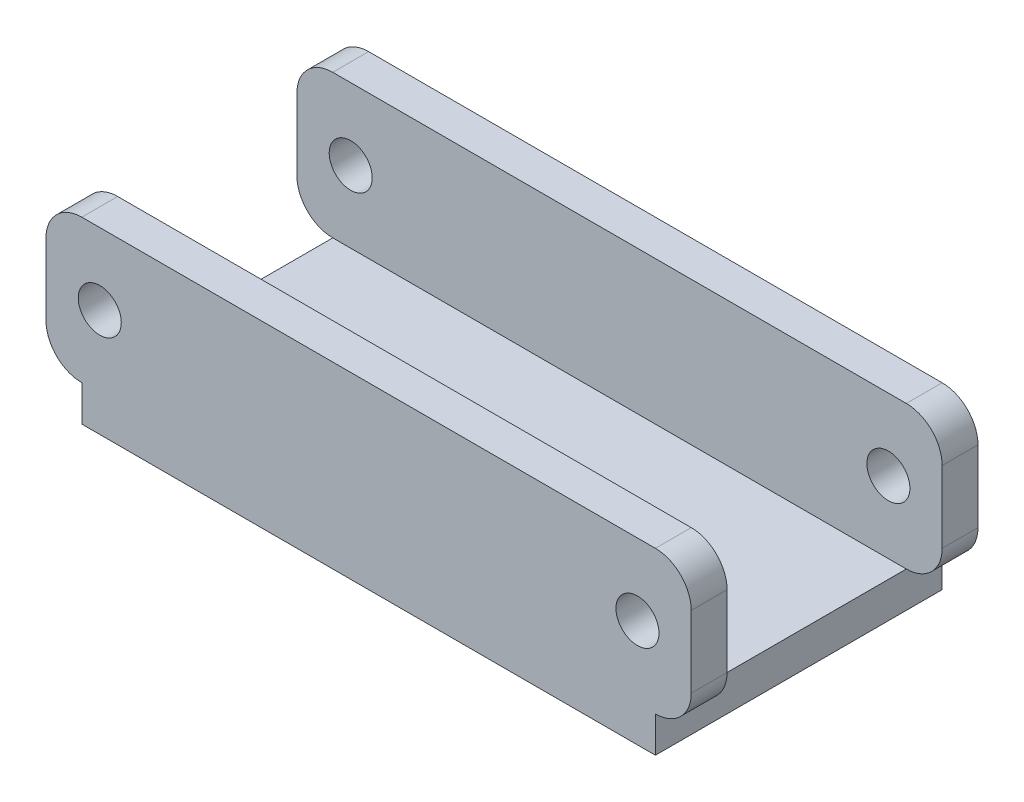
SolidWorks part; units mm, degrees
ref_plane "Front Plane" through (0, 0, 0) normal (0, 0, 1) x (1, 0, 0)
ref_plane "Top Plane" through (0, 0, 0) normal (0, 1, 0) x (1, 0, 0)
ref_plane "Right Plane" through (0, 0, 0) normal (1, 0, 0) x (0, 0, -1)
sketch "Sketch2" plane through (0, 0, 0) normal (0, 0, 1) x (1, 0, 0)
  line L1 (-450, -100) -> (450, -100)
  line L2 (-450, -100) -> (-450, 100)
  line L3 (-450, 100) -> (450, 100)
  line L4 (450, -100) -> (450, 100)
  line L5 (-450, -100) -> (450, 100) construction
  line L6 (-450, 100) -> (450, -100) construction
  point P0 (0, 0)
  dimension "D1" = 900
  dimension "D2" = 200
extrude "Boss-Extrude1" add sketch "Sketch2" along normal blind 400
sketch "Sketch3" plane through (0, 100, 0) normal (0, 1, 0) x (1, 0, 0)
  line L1 (-848.5274, -350) -> (848.5274, -350)
  line L2 (-848.5274, -350) -> (-848.5274, -50)
  line L3 (-848.5274, -50) -> (848.5274, -50)
  line L4 (848.5274, -350) -> (848.5274, -50)
  line L5 (-848.5274, -350) -> (848.5274, -50) construction
  line L6 (-848.5274, -50) -> (848.5274, -350) construction
  point P0 (0, -200)
  dimension "D1" = 300
extrude "Cut-Extrude1" cut sketch "Sketch3" against normal blind 400
fillet "Fillet1" radius 50 4 edges at (-450, -100, 375) (-450, 100, 375) (450, -100, 375) (450, 100, 375)
fillet "Fillet2" radius 50 4 edges at (450, -100, 25) (450, 100, 25) (-450, -100, 25) (-450, 100, 25)
sketch "  Sketch4" plane through (0, 0, 400) normal (0, 0, 1) x (1, 0, 0)
  line L2 (-450, 50) -> (-450, -50) construction
  line L3 (400, 100) -> (-400, 100) construction
  circle A0 centre (-375, 0) radius 30
  circle A18 centre (375, 0) radius 30
  circle A19 centre (-225, 0) radius 30 [skipped]
  circle A20 centre (-75, 0) radius 30 [skipped]
  circle A21 centre (75, 0) radius 30 [skipped]
  circle A22 centre (225, 0) radius 30 [skipped]
  dimension "D1" = 60
  dimension "D2" = 75
  dimension "D3" = 100
  dimension "D4" = 6
extrude "Cut-Extrude3" cut sketch "  Sketch4" against normal through all
sketch "Sketch4" plane through (0, -100, 0) normal (0, -1, 0) x (1, 0, 0)
  line L0 (400, 0) -> (450, 0) construction
  line L1 (-400, 400) -> (400, 400)
  line L2 (-400, 400) -> (-400, 0)
  line L3 (-400, 0) -> (400, 0)
  line L4 (400, 400) -> (400, 0)
  line L5 (-400, 0) -> (400, 0) construction
extrude "Boss-Extrude2" add sketch "Sketch4" along normal blind 50
